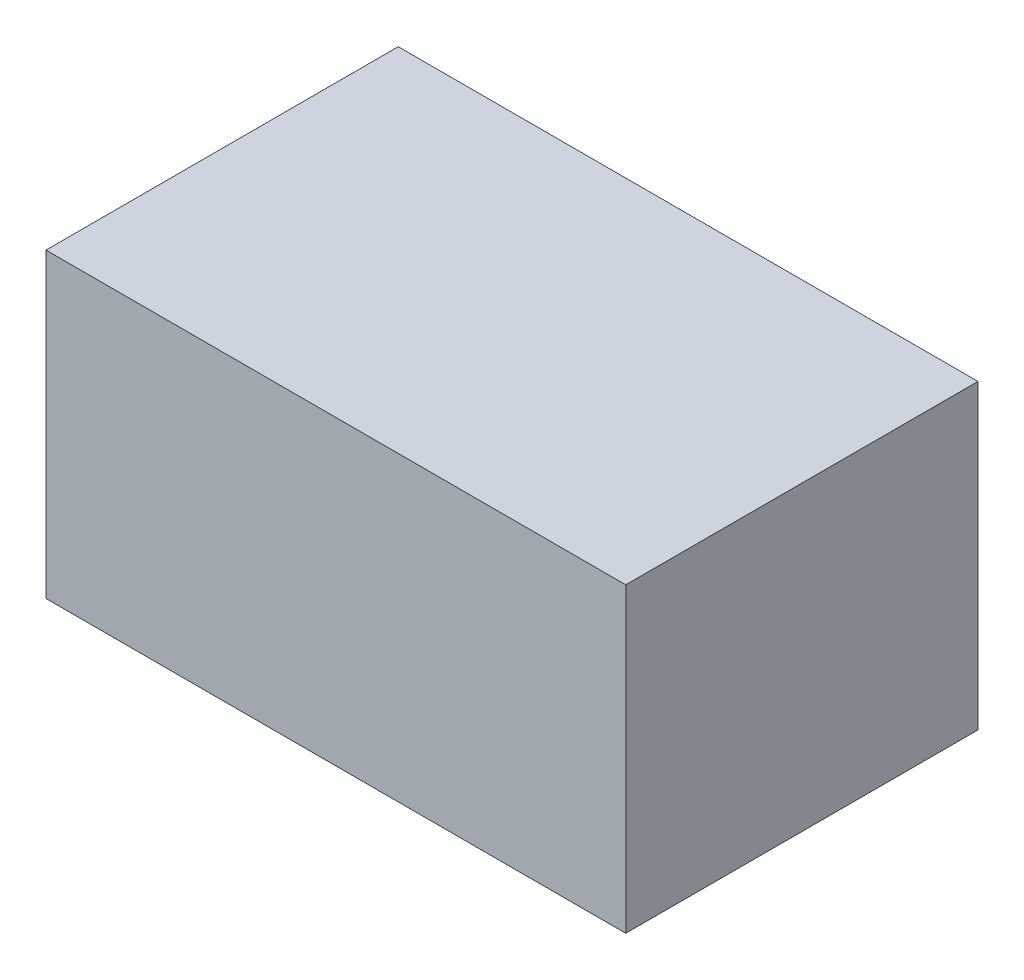
SolidWorks part; units mm, degrees
ref_plane "Front Plane" through (0, 0, 0) normal (0, 0, 1) x (1, 0, 0)
ref_plane "Top Plane" through (0, 0, 0) normal (0, 1, 0) x (1, 0, 0)
ref_plane "Right Plane" through (0, 0, 0) normal (1, 0, 0) x (0, 0, -1)
sketch "Sketch1" plane through (0, 0, 0) normal (0, 0, 1) x (1, 0, 0)
  line L0 (0, 0) -> (0, 65.6666) construction
  line L2 (-20.5736, 10.7096) -> (20.5736, 10.7096)
  line L3 (-20.5736, 10.7096) -> (-20.5736, -10.7096)
  line L4 (-20.5736, -10.7096) -> (20.5736, -10.7096)
  line L5 (20.5736, 10.7096) -> (20.5736, -10.7096)
  line L6 (-20.5736, 10.7096) -> (20.5736, -10.7096) construction
  line L7 (-20.5736, -10.7096) -> (20.5736, 10.7096) construction
  point P1 (0, 0)
extrude "Boss-Extrude1" add sketch "Sketch1" along normal blind 25
sketch "Sketch2" plane through (0, -10.7096, 0) normal (0, -1, 0) x (1, 0, 0)
  line L0 (0, 0) -> (0, 25) construction
  line L1 (-20.5736, 25) -> (20.5736, 25) construction
  circle A0 centre (0, 12.5) radius 7.5
  dimension "D1" = 15
extrude "Cut-Extrude1" cut sketch "Sketch2" against normal blind 10
scale "Scale1" bodies to scale 102 scale about centroid uniform scaling yes scale factor 3.5
